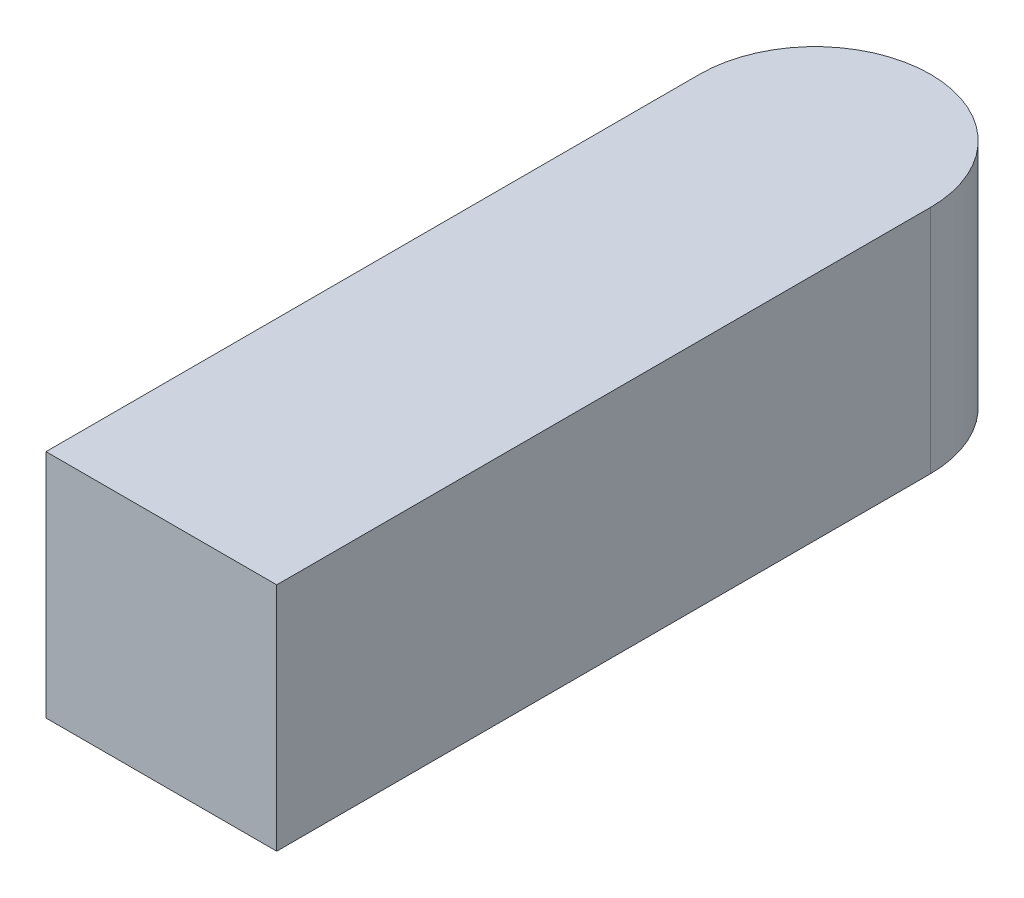
SolidWorks part; units mm, degrees
material "Plain Carbon Steel"
ref_plane "Front Plane" through (0, 0, 0) normal (0, 0, 1) x (1, 0, 0)
ref_plane "Top Plane" through (0, 0, 0) normal (0, 1, 0) x (1, 0, 0)
ref_plane "Right Plane" through (0, 0, 0) normal (1, 0, 0) x (0, 0, -1)
sketch "Sketch2" plane through (0, 0, 0) normal (0, 1, 0) x (1, 0, 0)
  line L0 (0, 0) -> (0, 8140.4332) construction
  line L2 (-1.5, 4.25) -> (-1.5, -4.25)
  line L3 (-1.5, -4.25) -> (1.5, -4.25)
  line L4 (1.5, 4.25) -> (1.5, -4.25)
  line L5 (-1.5, 4.25) -> (1.5, -4.25) construction
  line L6 (-1.5, -4.25) -> (1.5, 4.25) construction
  arc A0 (-1.5, 4.25) -> (1.5, 4.25) centre (0, 4.25) cw
  point P0 (0, 0)
  point P9 (0, 0)
  point P10 (0, 5.75)
  dimension "D1" = 3
  dimension "D2" = 10
extrude "Boss-Extrude1" add sketch "Sketch2" along normal mid plane 3
